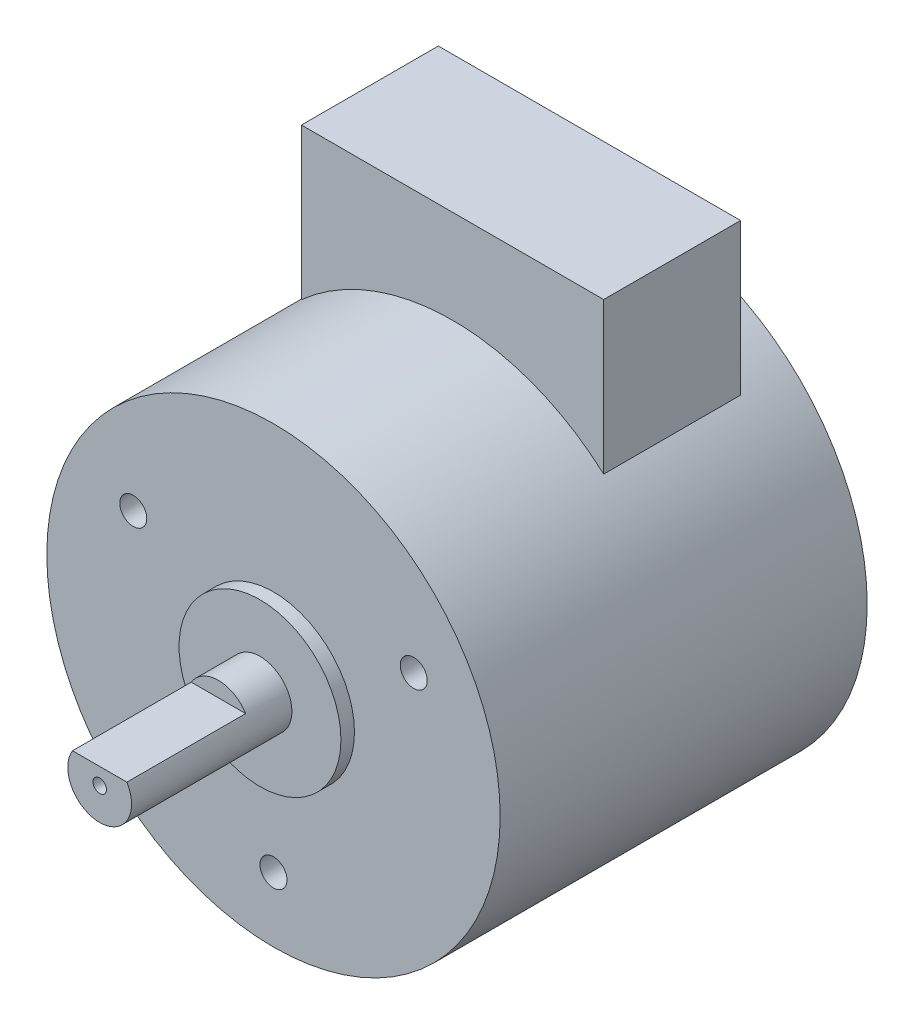
SolidWorks part; units mm, degrees
material "6061 Alloy"
ref_plane "Front Plane" through (0, 0, 0) normal (0, 0, 1) x (1, 0, 0)
ref_plane "Top Plane" through (0, 0, 0) normal (0, 1, 0) x (1, 0, 0)
ref_plane "Right Plane" through (0, 0, 0) normal (1, 0, 0) x (0, 0, -1)
sketch "Sketch1" plane through (0, 0, 0) normal (0, 0, 1) x (1, 0, 0)
  circle A0 centre (0, 0) radius 21
  dimension "D1" = 42
extrude "Boss-Extrude1" add sketch "Sketch1" along normal blind 34
sketch "Sketch2" plane through (0, 0, 34) normal (0, 0, 1) x (1, 0, 0)
  circle A0 centre (0, 0) radius 7.5
  dimension "D1" = 15
extrude "Boss-Extrude2" add sketch "Sketch2" along normal blind 1.25
sketch "Sketch3" plane through (0, 0, 35.25) normal (0, 0, 1) x (1, 0, 0)
  circle A0 centre (0, 0) radius 2.955
  dimension "D1" = 5.91
extrude "Boss-Extrude3" add sketch "Sketch3" along normal blind 14.85
sketch "Sketch4" plane through (0, 0, 50.1) normal (0, 0, 1) x (1, 0, 0)
  line L0 (-2.5189, 1.545) -> (2.5189, 1.545)
  line L1 (-3.3759, -2.955) -> (4.0899, -2.955) construction
  circle A0 centre (0, 0) radius 2.955 construction
  circle A1 centre (0, 0) radius 2.955 construction
  arc A2 (-2.5189, 1.545) -> (2.5189, 1.545) centre (0, 0) cw
  dimension "D1" = 4.5
extrude "Cut-Extrude1" cut sketch "Sketch4" against normal blind 11
sketch "Sketch5" plane through (0, 0, 50.1) normal (0, 0, 1) x (1, 0, 0)
  circle A0 centre (0, 0) radius 0.625
  dimension "D1" = 1.25
extrude "Cut-Extrude2" cut sketch "Sketch5" against normal blind 20
sketch "Sketch6" plane through (0, 0, 34) normal (0, 0, 1) x (1, 0, 0)
  circle A0 centre (0, -15) radius 1.25
  dimension "D1" = 2.5
  dimension "D2" = 15
extrude "Cut-Extrude3" cut sketch "Sketch6" against normal blind 4
pattern_circular "CirPattern1" count 3 over 360 about axis through (0, 0, 0) along (0, 0, 1) of "Cut-Extrude3"
sketch "Sketch9" plane through (0, 0, 34) normal (0, 0, 1) x (1, 0, 0)
  line L0 (-14, 15.6525) -> (-14, 29.66)
  line L1 (-14, 29.66) -> (14, 29.66)
  line L2 (14, 29.66) -> (14, 15.6525)
  line L3 (-31.1322, -21) -> (35.048, -21) construction
  circle A0 centre (0, 0) radius 21 construction
  arc A1 (-14, 15.6525) -> (14, 15.6525) centre (0, 0) cw
  dimension "D1" = 28
  dimension "D2" = 50.66
extrude "Boss-Extrude4" add sketch "Sketch9" against normal blind 12.68 from offset 16.59 offset against normal yes
sketch "Sketch10" plane through (0, 0, 0) normal (0, 0, -1) x (-1, 0, 0)
  circle A0 centre (0, 0) radius 4
  dimension "D1" = 8
extrude "Cut-Extrude4" cut sketch "Sketch10" against normal blind 1.66
